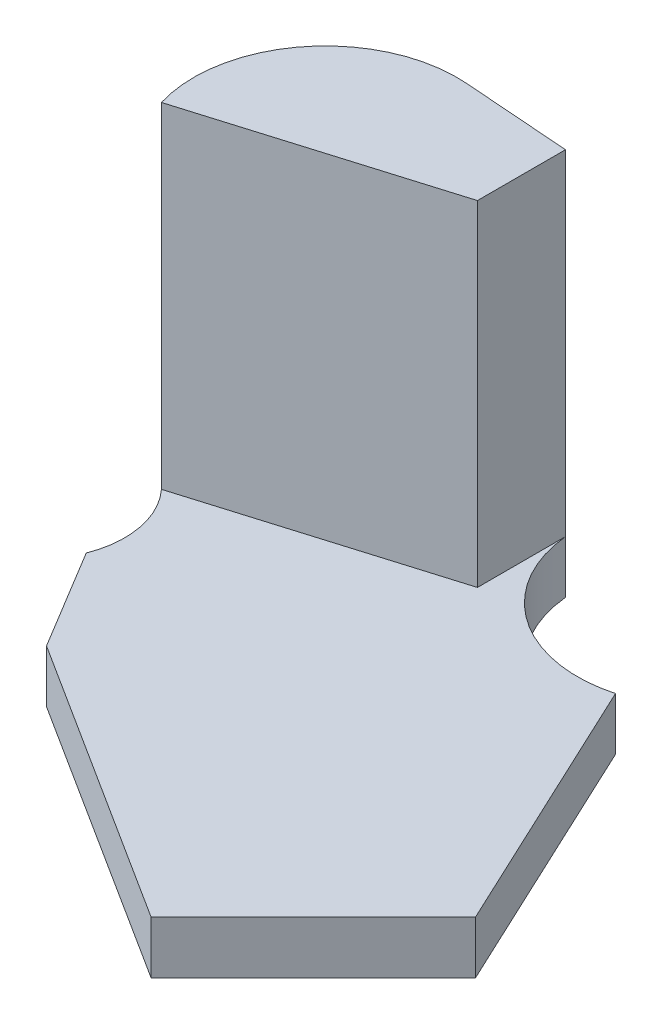
SolidWorks part; units mm, degrees
material "Custom Plastic"
ref_plane "X-Y Datum" through (0, 0, 0) normal (0, 0, 1) x (1, 0, 0)
ref_plane "X-Z Datum" through (0, 0, 0) normal (0, 1, 0) x (1, 0, 0)
ref_plane "Y-Z Datum" through (0, 0, 0) normal (1, 0, 0) x (0, 0, -1)
sketch "Sketch2" plane through (0, -35.9968, 0) normal (0, -1, 0) x (1, 0, 0)
  line L0 (-512.959, 54.0747) -> (-477.7843, 43.4991)
  line L1 (-477.7843, 43.4991) -> (-477.7843, 30.7504)
  line L2 (-477.7843, 30.7504) -> (-493.2979, 29.5925)
  arc A0 (-512.959, 54.0747) -> (-493.2979, 29.5925) centre (-494.7157, 48.5897) ccw
  arc A1 (-512.959, 54.0747) -> (-493.2979, 29.5925) centre (-494.7157, 48.5897) ccw construction
extrude "Boss-Extrude1" add sketch "Sketch2" along normal up to surface (48.514 mm away)
sketch "Sketch3" plane through (0, -84.5108, 0) normal (0, -1, 0) x (1, 0, 0)
  line L0 (-460.0553, 108.4707) -> (-436.5905, 84.9748)
  line L1 (-436.5905, 84.9748) -> (-454.4905, 46.8031)
  line L2 (-460.0553, 108.4707) -> (-501.6533, 82.0249)
  line L3 (-501.6533, 82.0249) -> (-510.4193, 67.5043)
  line L4 (-493.2979, 29.5925) -> (-477.7843, 30.7504)
  arc A0 (-477.7843, 30.7504) -> (-454.4905, 46.8031) centre (-459.3596, 28.9416) cw
  arc A1 (-461.5052, 41.4591) -> (-470.2931, 35.403) centre (-459.3596, 28.9416) ccw construction
  arc A2 (-512.959, 54.0747) -> (-493.2979, 29.5925) centre (-494.7157, 48.5897) ccw
  arc A3 (-512.959, 54.0747) -> (-493.2979, 29.5925) centre (-494.7157, 48.5897) ccw construction
  arc A4 (-510.4193, 67.5043) -> (-512.959, 54.0747) centre (-522.4527, 62.825) cw
extrude "Boss-Extrude2" add sketch "Sketch3" along normal up to surface (7.62 mm away)
